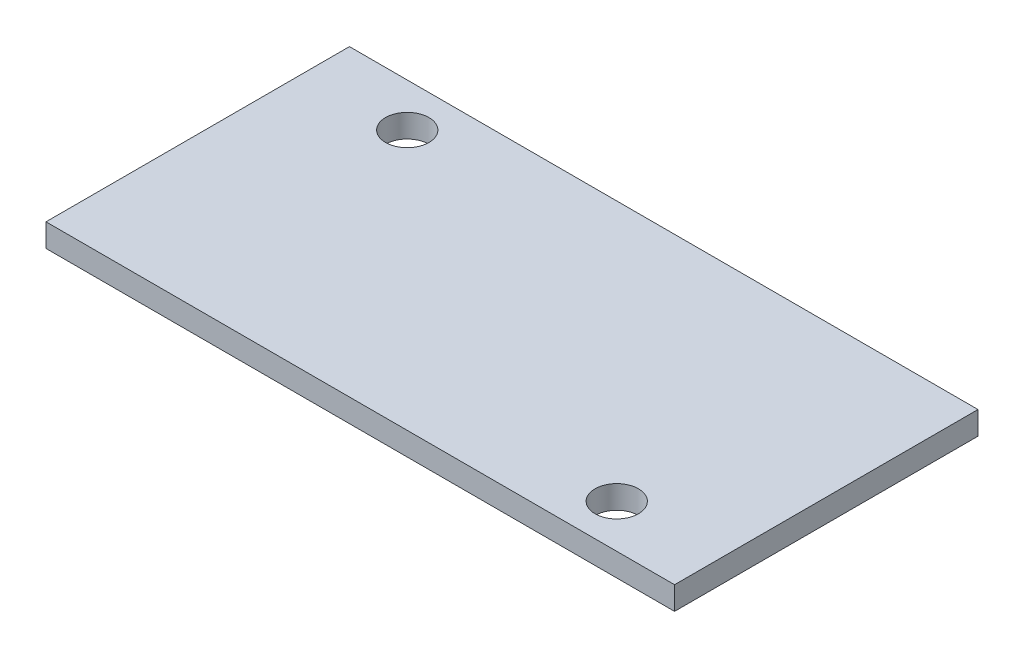
SolidWorks part; units mm, degrees
ref_plane "前视基准面" through (0, 0, 0) normal (0, 0, 1) x (1, 0, 0)
ref_plane "上视基准面" through (0, 0, 0) normal (0, 1, 0) x (1, 0, 0)
ref_plane "右视基准面" through (0, 0, 0) normal (1, 0, 0) x (0, 0, -1)
sketch "草图1" plane through (0, 0, 0) normal (0, 1, 0) x (1, 0, 0)
  line L0 (0, -18.7925) -> (0, 34.5365) construction
  line L1 (-21.75, 10.5) -> (21.75, 10.5)
  line L2 (-21.75, 10.5) -> (-21.75, -10.5)
  line L3 (-21.75, -10.5) -> (21.75, -10.5)
  line L4 (21.75, 10.5) -> (21.75, -10.5)
  line L5 (-48.0579, 0) -> (50.1007, 0) construction
  dimension "D1" = 43.5
  dimension "D2" = 21
extrude "凸台-拉伸1" add sketch "草图1" along normal blind 1.6
sketch "草图2" plane through (0, 1.6, 0) normal (0, 1, 0) x (1, 0, 0)
  line L0 (-21.75, 10.5) -> (-21.75, -10.5) construction
  line L1 (21.75, 10.5) -> (-21.75, 10.5) construction
  line L2 (21.75, -10.5) -> (21.75, 10.5) construction
  line L4 (-21.75, -10.5) -> (21.75, -10.5) construction
  circle A0 centre (-14.75, 7.5) radius 1.5
  circle A1 centre (14.75, -7.5) radius 1.5
  point P12 (14.03, -10.5)
  dimension "D1" = 3
  dimension "D4" = 3
  dimension "D2" = 7
  dimension "D3" = 3
  dimension "D5" = 7
  dimension "D6" = 3
extrude "切除-拉伸1" cut sketch "草图2" against normal blind 10
